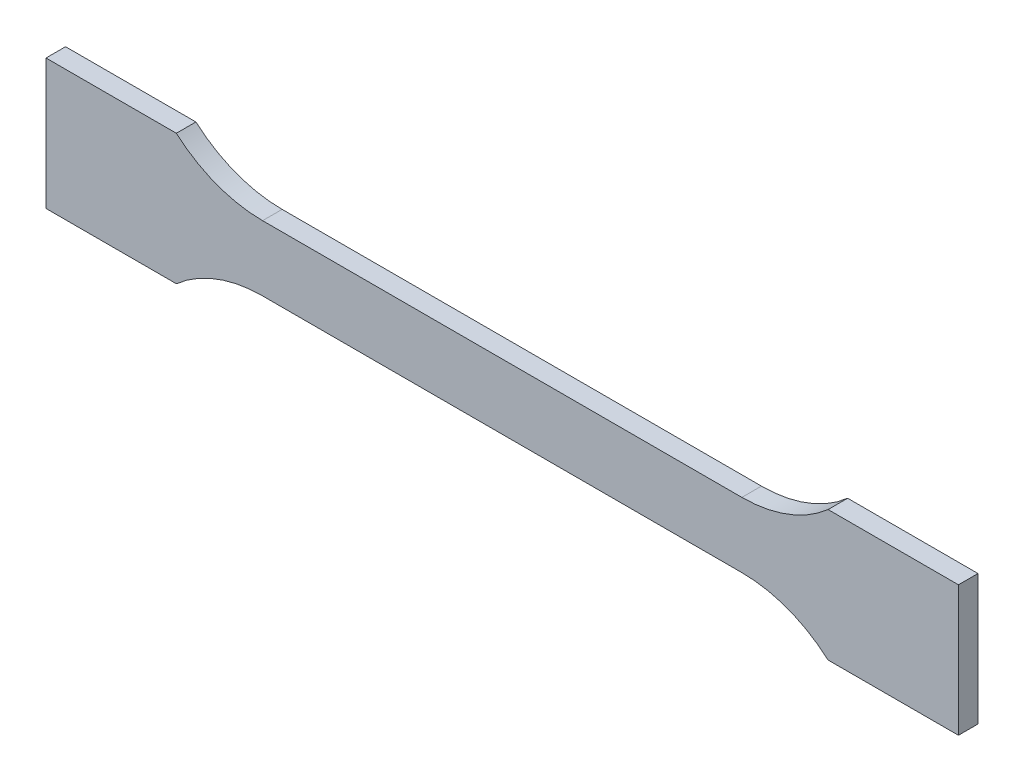
SolidWorks part; units mm, degrees
ref_plane "Plan de face" through (0, 0, 0) normal (0, 0, 1) x (1, 0, 0)
ref_plane "Plan de dessus" through (0, 0, 0) normal (0, 1, 0) x (1, 0, 0)
ref_plane "Plan de droite" through (0, 0, 0) normal (1, 0, 0) x (0, 0, -1)
sketch "Esquisse1" plane through (0, 0, 0) normal (0, 0, 1) x (1, 0, 0)
  line L0 (0, 20) -> (0, 0)
  line L1 (0, 10) -> (70, 10) construction
  line L2 (0, 0) -> (20, 0)
  line L3 (70, 15) -> (70, 5)
  line L4 (33.2288, 5) -> (70, 5)
  line L5 (33.2288, 15) -> (70, 15)
  line L6 (0, 20) -> (20, 20)
  arc A0 (20, 20) -> (33.2288, 15) centre (33.2288, 35) ccw
  arc A1 (20, 0) -> (33.2288, 5) centre (33.2288, -15) cw
  dimension "D2" = 20
  dimension "D1" = 10
  dimension "D3" = 20
  dimension "D4" = 5
  dimension "D5" = 70
extrude "Boss.-Extru.1" add sketch "Esquisse1" along normal blind 3
mirror "Symétrie7" about plane through (70, 15, 3) normal (-1, 0, 0) of "Boss.-Extru.1"
